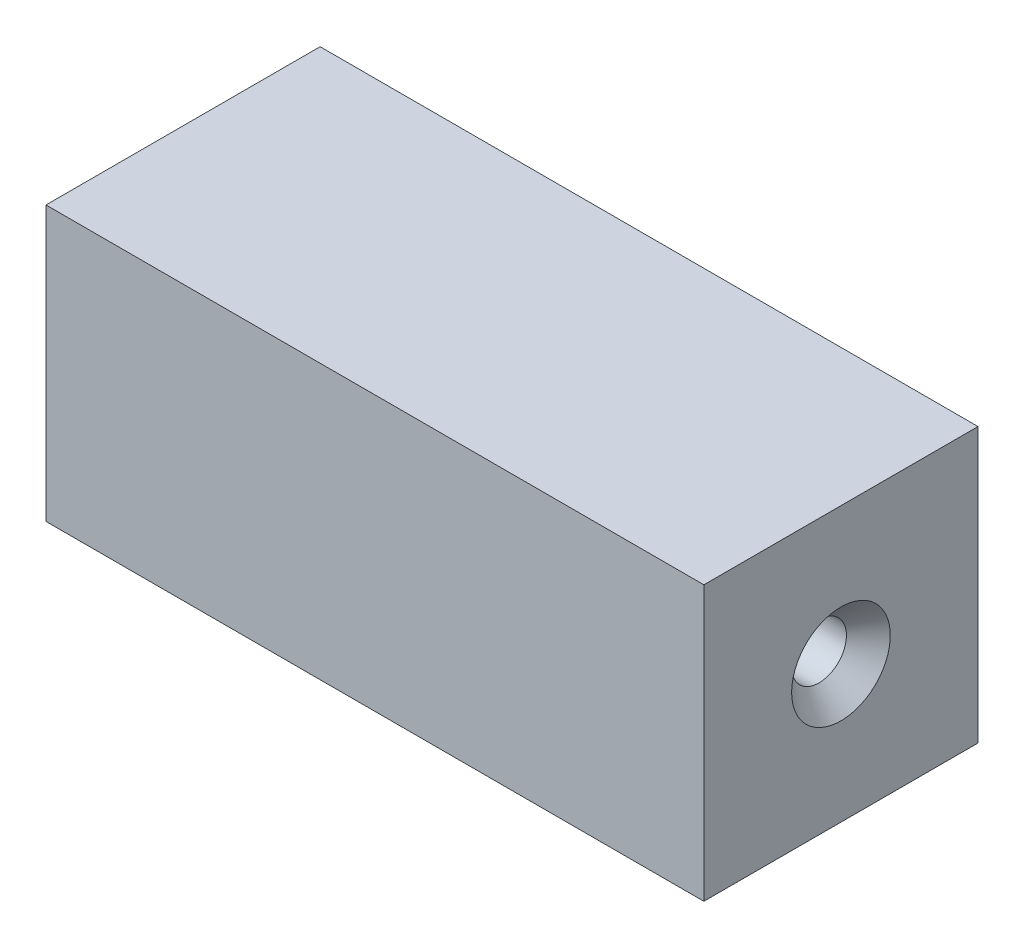
SolidWorks part; units mm, degrees
ref_plane "Front Plane" through (0, 0, 0) normal (0, 0, 1) x (1, 0, 0)
ref_plane "Top Plane" through (0, 0, 0) normal (0, 1, 0) x (1, 0, 0)
ref_plane "Right Plane" through (0, 0, 0) normal (1, 0, 0) x (0, 0, -1)
sketch "Sketch1" plane through (0, 0, 0) normal (1, 0, 0) x (0, 0, -1)
  line L1 (-15.875, -15.875) -> (15.875, -15.875)
  line L2 (-15.875, -15.875) -> (-15.875, 15.875)
  line L3 (-15.875, 15.875) -> (15.875, 15.875)
  line L4 (15.875, -15.875) -> (15.875, 15.875)
  line L5 (-15.875, -15.875) -> (15.875, 15.875) construction
  line L6 (-15.875, 15.875) -> (15.875, -15.875) construction
  point P0 (0, 0)
  dimension "D1" = 31.75
  dimension "D2" = 31.75
extrude "Boss-Extrude1" add sketch "Sketch1" along normal blind 76.2 contours L3 L4 L1 L2
sketch "Sketch2" plane through (76.2, 0, 0) normal (1, 0, 0) x (0, 0, -1)
  circle A0 centre (0, 0) radius 3.175
  dimension "D1" = 6.35
extrude "Cut-Extrude1" cut sketch "Sketch2" against normal blind 25.4
chamfer "Chamfer1" distance 2.54 angle 45 1 edges at (76.2, 0, -3.175)
